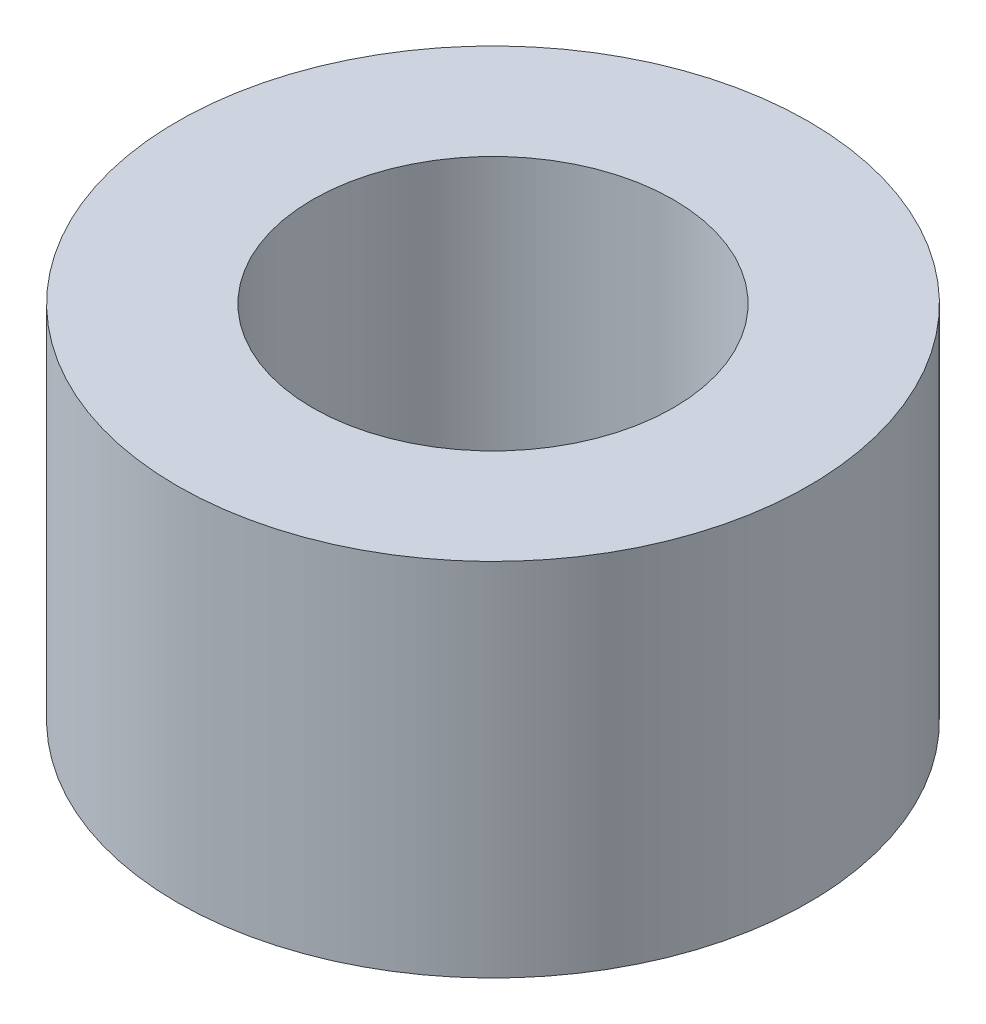
SolidWorks part; units mm, degrees
material "Copper"
ref_plane "Front Plane" through (0, 0, 0) normal (0, 0, 1) x (1, 0, 0)
ref_plane "Top Plane" through (0, 0, 0) normal (0, 1, 0) x (1, 0, 0)
ref_plane "Right Plane" through (0, 0, 0) normal (1, 0, 0) x (0, 0, -1)
sketch "Sketch1" plane through (0, 0, 0) normal (0, 1, 0) x (1, 0, 0)
  circle A0 centre (0, 0) radius 10
  circle A1 centre (0, 0) radius 17.5
  dimension "D1" = 20
  dimension "D2" = 35
extrude "Boss-Extrude1" add sketch "Sketch1" along normal mid plane 20
